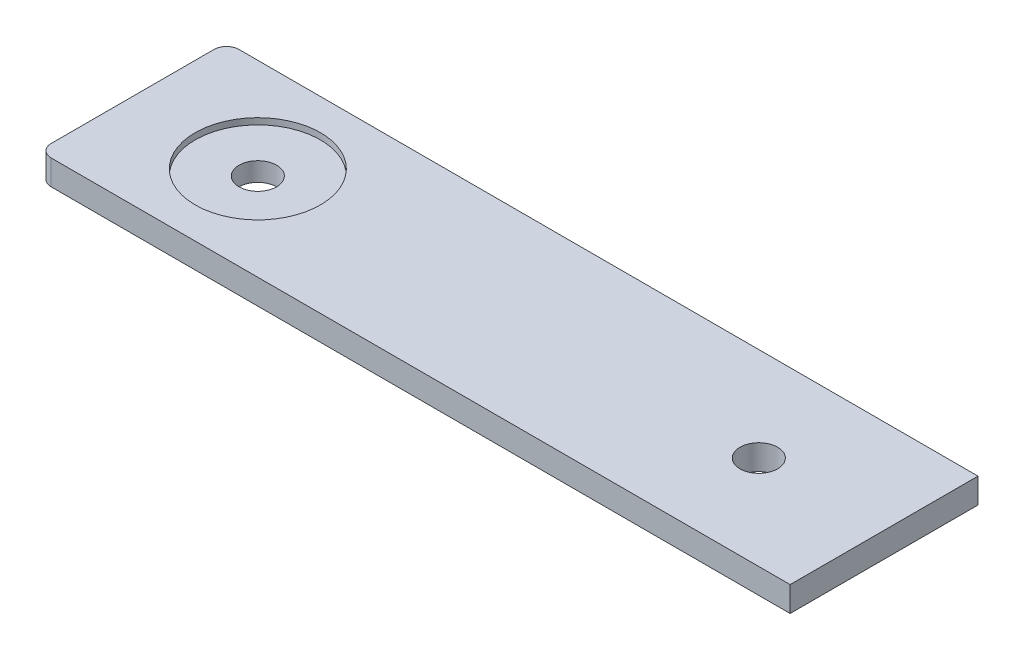
SolidWorks part; units mm, degrees
ref_plane "Front Plane" through (0, 0, 0) normal (0, 0, 1) x (1, 0, 0)
ref_plane "Top Plane" through (0, 0, 0) normal (0, 1, 0) x (1, 0, 0)
ref_plane "Right Plane" through (0, 0, 0) normal (1, 0, 0) x (0, 0, -1)
sketch "Sketch1" plane through (0, 0, 0) normal (0, 1, 0) x (1, 0, 0)
  line L0 (0, 7.5) -> (60, 7.5)
  line L1 (0, 0) -> (60, 0)
  line L2 (0, 0) -> (0, 15)
  line L3 (0, 15) -> (60, 15)
  line L4 (60, 0) -> (60, 15)
  circle A0 centre (10, 7.5) radius 1.5
  circle A1 centre (50, 7.5) radius 1.5
  dimension "D3" = 10
  dimension "D4" = 40
  dimension "D1" = 15
  dimension "D2" = 60
extrude "Boss-Extrude1" add sketch "Sketch1" along normal blind 2 contours A1 L0 A0 L2 L1 L4 | A1 L0 L4 L3 L2 A0
sketch "Sketch2" plane through (0, 2, 0) normal (0, 1, 0) x (1, 0, 0)
  circle A0 centre (10, 7.5) radius 5
extrude "Cut-Extrude1" cut sketch "Sketch2" against normal blind 0.5
fillet "Fillet1" radius 1 2 edges at (0, 1, -15) (0, 1, 0)
